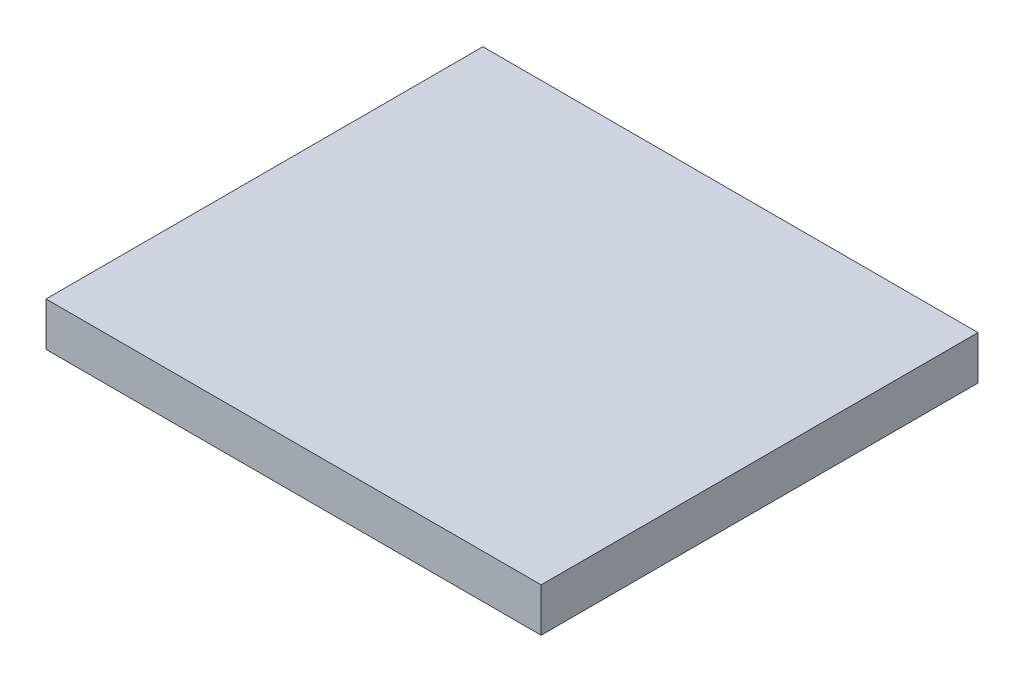
SolidWorks part; units mm, degrees
ref_plane "Front Plane" through (0, 0, 0) normal (0, 0, 1) x (1, 0, 0)
ref_plane "Top Plane" through (0, 0, 0) normal (0, 1, 0) x (1, 0, 0)
ref_plane "Right Plane" through (0, 0, 0) normal (1, 0, 0) x (0, 0, -1)
ref_plane "Plane1" through (0, 0, 150) normal (0, 0, 1) x (1, 0, 0)
sketch "Sketch1" plane through (0, 0, 0) normal (0, 0, 1) x (1, 0, 0)
  line L1 (-39.1379, 4.6983) -> (130.8621, 4.6983)
  line L2 (-39.1379, 4.6983) -> (-39.1379, -10.3017)
  line L3 (-39.1379, -10.3017) -> (130.8621, -10.3017)
  line L4 (130.8621, 4.6983) -> (130.8621, -10.3017)
  dimension "D1" = 15
  dimension "D2" = 170
sketch "Sketch4" plane through (0, 0, 150) normal (0, 0, 1) x (1, 0, 0)
  line L1 (-54.5924, 21.7437) -> (115.4076, 21.7437)
  line L2 (-54.5924, 21.7437) -> (-54.5924, -28.2563)
  line L3 (-54.5924, -28.2563) -> (115.4076, -28.2563)
  line L4 (115.4076, 21.7437) -> (115.4076, -28.2563)
  circle A0 centre (50.5309, 13.4437) radius 3.2
  circle A1 centre (155.6542, 13.4437) radius 3.2
  circle A2 centre (155.6542, -18.9563) radius 3.2
  circle A3 centre (50.5309, -18.9563) radius 3.2
  point P4 (188.0926, -3.2563)
  dimension "D5" = 6.4
  dimension "D1" = 50
  dimension "D2" = 170
  dimension "D3" = 25
  dimension "D4" = 242.685
  dimension "D6" = 32.4
  dimension "D7" = 105.1233
  dimension "D10" = 105.1233
  dimension "D11" = 8.3
  dimension "D8" = 2
  dimension "D9" = 2
sketch "Sketch5" plane through (0, 0, 0) normal (0, 0, 1) x (1, 0, 0)
  line L1 (-54.5924, 21.7437) -> (260.7776, 21.7437)
  line L2 (-54.5924, 21.7437) -> (-54.5924, -28.2563)
  line L3 (-54.5924, -28.2563) -> (260.7776, -28.2563)
  line L4 (260.7776, 21.7437) -> (260.7776, -28.2563)
  circle A0 centre (50.5309, 13.4437) radius 3.2
  circle A1 centre (155.6542, 13.4437) radius 3.2
  circle A2 centre (155.6542, -18.9563) radius 3.2
  circle A3 centre (50.5309, -18.9563) radius 3.2
  point P4 (188.0926, -3.2563)
  dimension "D5" = 6.4
  dimension "D1" = 50
  dimension "D2" = 315.37
  dimension "D3" = 25
  dimension "D4" = 242.685
  dimension "D6" = 32.4
  dimension "D7" = 105.1233
  dimension "D10" = 105.1233
  dimension "D11" = 8.3
  dimension "D12" = 110.0031
  dimension "D8" = 2
  dimension "D9" = 2
extrude "middle" add sketch "Sketch1" along normal blind 150
